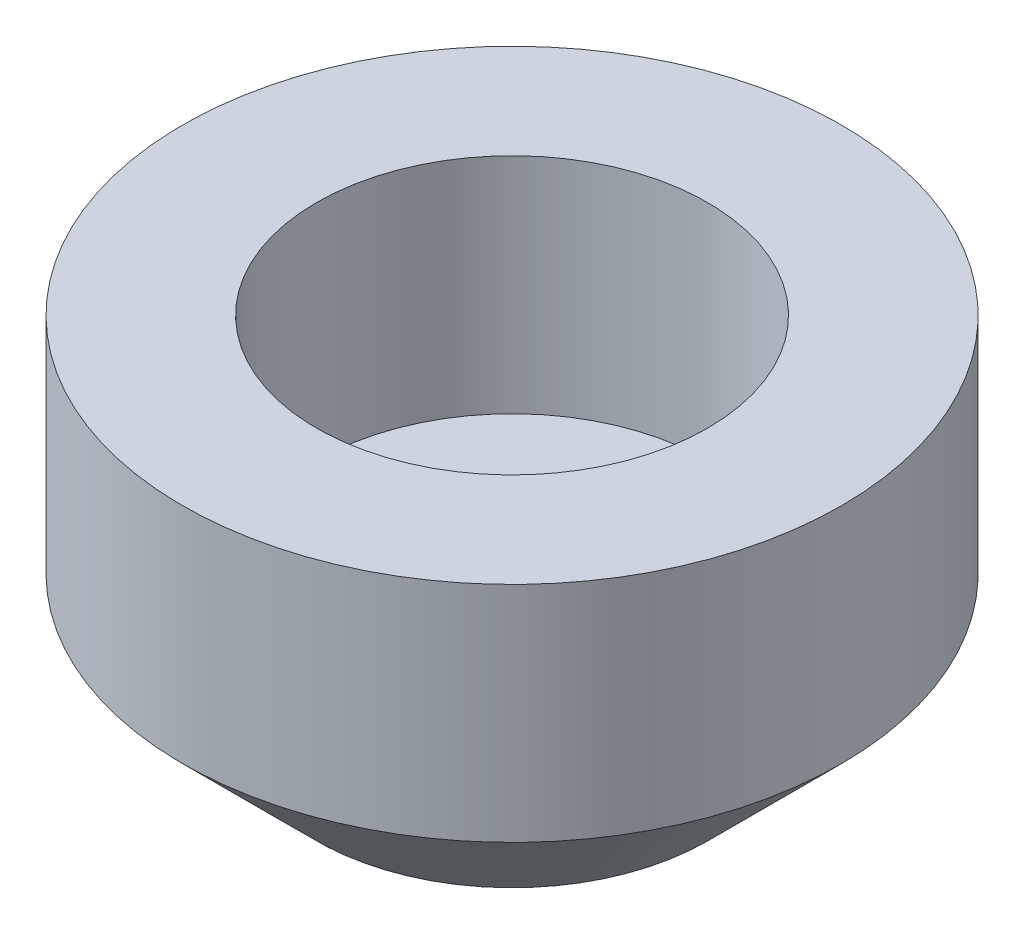
SolidWorks part; units mm, degrees
ref_plane "Front Plane" through (0, 0, 0) normal (0, 0, 1) x (1, 0, 0)
ref_plane "Top Plane" through (0, 0, 0) normal (0, 1, 0) x (1, 0, 0)
ref_plane "Right Plane" through (0, 0, 0) normal (1, 0, 0) x (0, 0, -1)
sketch "Sketch1" plane through (0, 0, 0) normal (0, 0, 1) x (1, 0, 0)
  line L3 (-4.375, 0) -> (4.375, 0) construction
  line L4 (4.375, 5) -> (-4.375, 5) construction
  line L5 (-4.375, 5) -> (-4.375, 0) construction
  line L14 (0, 0) -> (-4.375, 0)
  line L15 (0, -3) -> (0, 0)
  line L16 (-4.375, -3) -> (0, -3)
  line L17 (-7.375, 0) -> (-4.375, -3)
  line L18 (-7.375, 5) -> (-7.375, 0)
  line L19 (-4.375, 5) -> (-7.375, 5)
  line L20 (-4.375, 0) -> (-4.375, 5)
  point P7 (0, 0)
  point P8 (0, 0)
  point P11 (0, 0)
  point P18 (-7.375, 0)
  point P19 (-4.375, -3.2393)
  dimension "D1" = 3
  dimension "D2" = 135
revolve "Revolve1" add sketch "Sketch1" angle 360 about L15
